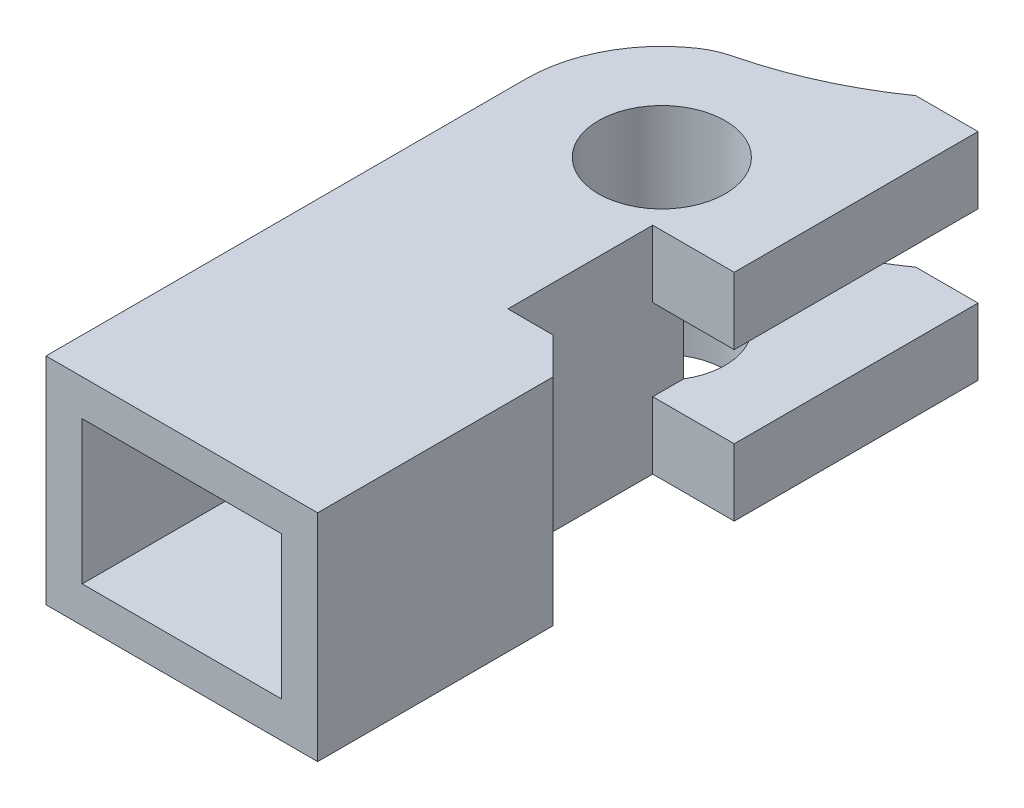
SolidWorks part; units mm, degrees
ref_plane "Front Plane" through (0, 0, 0) normal (0, 0, 1) x (1, 0, 0)
ref_plane "Top Plane" through (0, 0, 0) normal (0, 1, 0) x (1, 0, 0)
ref_plane "Right Plane" through (0, 0, 0) normal (1, 0, 0) x (0, 0, -1)
sketch "Sketch3" plane through (0, 0, 0) normal (0, 1, 0) x (1, 0, 0)
  line L0 (7.5, 0) -> (7.5, 12.6575)
  line L1 (7.5, 12.6575) -> (4.8161, 12.6575)
  line L2 (7.5, 0) -> (7.5, -3.5009)
  line L3 (7.5, -3.5009) -> (3, -3.5009)
  line L4 (-7.5, -16.5009) -> (-7.5, 0)
  line L5 (3, -3.5009) -> (3, -11.5009)
  line L6 (3, -11.5009) -> (7.5, -11.5009)
  line L7 (7.5, -11.5009) -> (7.5, -16.5009)
  line L8 (7.5, -16.5009) -> (-7.5, -16.5009)
  circle A0 centre (0, 0) radius 3.5
  arc A1 (-3.4535, 6.6576) -> (-7.5, 0) centre (0, 0) ccw
  arc A2 (-1.1959, 9.243) -> (-3.4535, 6.6576) centre (-9.4263, 14.1514) cw
  arc A3 (4.8161, 12.6575) -> (-1.1959, 9.243) centre (4.8161, 5.6575) ccw
  point P16 (0, 0)
  dimension "D1" = 7
  dimension "D2" = 15
  dimension "D3" = 4.5
  dimension "D4" = 8
  dimension "D5" = 5
  dimension "D6" = 4.5
extrude "Boss-Extrude2" add sketch "Sketch3" along normal blind 11.9
sketch "Sketch4" plane through (0, 0, -12.6575) normal (0, 0, -1) x (-1, 0, 0)
  line L0 (-7.5, 11.9) -> (-7.5, 0) construction
  line L1 (-12, 3.7) -> (-3, 3.7)
  line L2 (-12, 3.7) -> (-12, 8.2)
  line L3 (-12, 8.2) -> (-3, 8.2)
  line L4 (-3, 3.7) -> (-3, 8.2)
  line L5 (-12, 3.7) -> (-3, 8.2) construction
  line L6 (-12, 8.2) -> (-3, 3.7) construction
  point P0 (-7.5, 5.95)
  dimension "D1" = 4.5
  dimension "D2" = 9
extrude "Cut-Extrude1" cut sketch "Sketch4" against normal up to surface (16.1584 mm away) up to face at (5.25, 5.95, 3.5009)
sketch "Sketch5" plane through (0, 0, 16.5009) normal (0, 0, 1) x (1, 0, 0)
  line L4 (-5.5, 9.9) -> (-5.5, 2)
  line L5 (-5.5, 2) -> (5.5, 2)
  line L6 (5.5, 2) -> (5.5, 9.9)
  line L7 (5.5, 9.9) -> (-5.5, 9.9)
  line L8 (-7.5, 0) -> (7.5, 0)
  line L9 (7.5, 0) -> (7.5, 11.9)
  line L10 (7.5, 11.9) -> (-7.5, 11.9)
  line L11 (-7.5, 11.9) -> (-7.5, 0)
  line L12 (-7.5, 0) -> (7.5, 0)
  line L13 (7.5, 0) -> (7.5, 11.9)
  line L14 (7.5, 11.9) -> (-7.5, 11.9)
  line L15 (-7.5, 11.9) -> (-7.5, 0)
  dimension "D1" = 0
  dimension "D2" = 2
extrude "Boss-Extrude3" add sketch "Sketch5" along normal blind 10
sketch "Sketch6" plane through (7.5, 0, 0) normal (1, 0, 0) x (0, 0, -1)
  line L0 (-3.5009, 11.9) -> (12.6575, 11.9) construction
  line L1 (12.6575, 0) -> (9.9575, 0)
  line L2 (12.6575, 0) -> (12.6575, 11.9)
  line L3 (12.6575, 11.9) -> (9.9575, 11.9)
  line L4 (9.9575, 0) -> (9.9575, 11.9)
  dimension "D1" = 2.7
extrude "Cut-Extrude2" cut sketch "Sketch6" against normal through all both and the other way through all
sketch "Sketch7" plane through (0, 0, 0) normal (0, -1, 0) x (1, 0, 0)
  line L0 (-0.7075, -9.9575) -> (7.5, -9.9575) construction
  line L1 (-3.4535, -6.6576) -> (-1.7799, -9.6785)
  line L2 (-1.7799, -9.6785) -> (0.4717, -11.2746)
  line L3 (0.4717, -11.2746) -> (4.0672, -10.0622)
  line L4 (4.0672, -10.0622) -> (4.0672, -9.9575)
  arc A0 (-3.4535, -6.6576) -> (4.0672, -9.9575) centre (-7.8684, -26.9395) cw
extrude "Cut-Extrude3" cut sketch "Sketch7" against normal through all both and the other way through all
fillet "Fillet1" radius 4 1 edges at (-3.4535, 5.95, -6.6576)
chamfer "Chamfer1" distance 2 angle 45 1 edges at (7.5, 5.95, 11.5009)
